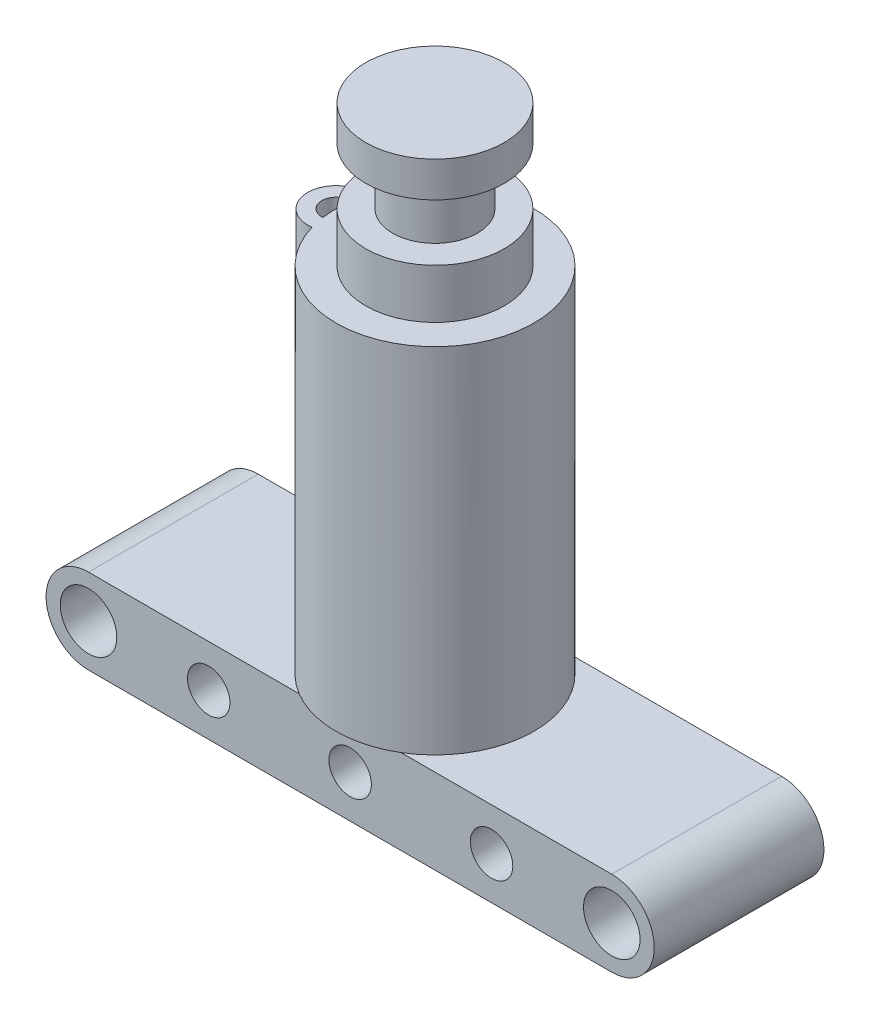
SolidWorks part; units mm, degrees
ref_plane "前视基准面" through (0, 0, 0) normal (0, 0, 1) x (1, 0, 0)
ref_plane "上视基准面" through (0, 0, 0) normal (0, 1, 0) x (1, 0, 0)
ref_plane "右视基准面" through (0, 0, 0) normal (1, 0, 0) x (0, 0, -1)
other "Configuration Table"
sketch "草图1" plane through (0, 0, 0) normal (0, 0, 1) x (1, 0, 0)
  line L0 (0, 0) -> (37, 0) construction
  line L1 (0, 3) -> (37, 3)
  line L2 (0, -3) -> (37, -3)
  arc A0 (0, 3) -> (0, -3) centre (0, 0) ccw
  arc A1 (37, -3) -> (37, 3) centre (37, 0) ccw
  circle A2 centre (0, 0) radius 2
  circle A3 centre (37, 0) radius 2
  point P3 (18.5, 0)
  dimension "D2" = 3
  dimension "D3" = 4
  dimension "D4" = 4
  dimension "D1" = 37
extrude "凸台-拉伸1" add sketch "草图1" along normal blind 12
sketch "草图2" plane through (0, 0, 12) normal (0, 0, 1) x (1, 0, 0)
  line L0 (18.5, 3) -> (18.5, -3) construction
  line L1 (37, 3) -> (0, 3) construction
  line L2 (0, -3) -> (37, -3) construction
  circle A0 centre (18.5, 0) radius 1.5
  dimension "D1" = 3
extrude "切除-拉伸1" cut sketch "草图2" against normal through all
pattern_linear "阵列(线性)1" count 2 spacing 10 along (-1, 0, 0) count 2 spacing 10 along (1, 0, 0) of "切除-拉伸1"
sketch "草图4" plane through (0, 3, 0) normal (0, 1, 0) x (1, 0, 0)
  line L0 (18.5, 1) -> (18.5, -12) construction
  line L2 (37, -12) -> (0, -12) construction
  line L4 (37, 0) -> (0, 0) construction
  circle A0 centre (18.5, -6) radius 7
  dimension "D1" = 14
  dimension "D2" = 6
extrude "凸台-拉伸2" add sketch "草图4" along normal blind 25
sketch "草图6" plane through (0, 0, 0) normal (0, 0, 1) x (1, 0, 0)
  line L0 (-68.7058, 150.2252) -> (705.9609, 150.2252) construction
sketch "草图7" plane through (0, 28, 0) normal (0, 1, 0) x (1, 0, 0)
  circle A0 centre (11.5, -6) radius 2
  circle A2 centre (11.5, -6) radius 1
  circle A3 centre (18.5, -6) radius 7 construction
  dimension "D1" = 4
  dimension "D2" = 2
extrude "凸台-拉伸3" add sketch "草图7" against normal blind 4
ref_plane "基准面1" through (0, 14, 0) normal (0, -1, 0) x (-1, 0, 0)
sketch "草图9" plane through (0, 14, 0) normal (0, -1, 0) x (-1, 0, 0)
  circle A0 centre (-18.5, -6) radius 7 construction
  arc A1 (-11.5714, -6.9974) -> (-11.5714, -5.0026) centre (-11.5, -6) ccw construction
  arc A2 (-11.7857, -7.9795) -> (-11.7857, -4.0205) centre (-11.5, -6) ccw construction
  arc A3 (-11.7857, -7.9795) -> (-11.5714, -6.9974) centre (-18.5, -6) ccw
  arc A4 (-11.5714, -6.9974) -> (-11.5714, -5.0026) centre (-11.5, -6) ccw
  arc A5 (-11.7857, -7.9795) -> (-11.7857, -4.0205) centre (-11.5, -6) ccw
  arc A6 (-11.5714, -5.0026) -> (-11.7857, -4.0205) centre (-18.5, -6) ccw
extrude "凸台-拉伸5" add sketch "草图9" along normal mid plane 4
sketch "草图10" plane through (0, 28, 0) normal (0, 1, 0) x (1, 0, 0)
  circle A0 centre (18.5, -6) radius 4.9
  dimension "D1" = 9.8
extrude "凸台-拉伸6" add sketch "草图10" along normal blind 10
sketch "草图11" plane through (0, 28, 0) normal (0, 1, 0) x (1, 0, 0)
  circle A2 centre (18.5, -6) radius 5
sketch "草图12" plane through (0, 0, 0) normal (0, 0, 1) x (1, 0, 0)
  line L0 (18.5, 38) -> (18.5, 32.1361) construction
  line L1 (23.4, 38) -> (13.6, 38) construction
  circle A0 centre (18.5, 34) radius 1.5
  dimension "D1" = 3
  dimension "D2" = 4
ref_plane "基准面2" through (0, 35.5, 0) normal (0, 1, 0) x (1, 0, 0)
sketch "草图13" plane through (0, 35.5, 0) normal (0, 1, 0) x (1, 0, 0)
  circle A0 centre (18.5, -6) radius 4.9 construction
  circle A1 centre (18.5, -6) radius 4.9
  circle A3 centre (18.5, -6) radius 3
  dimension "D1" = 6
extrude "切除-拉伸2" cut sketch "草图13" against normal blind 4
